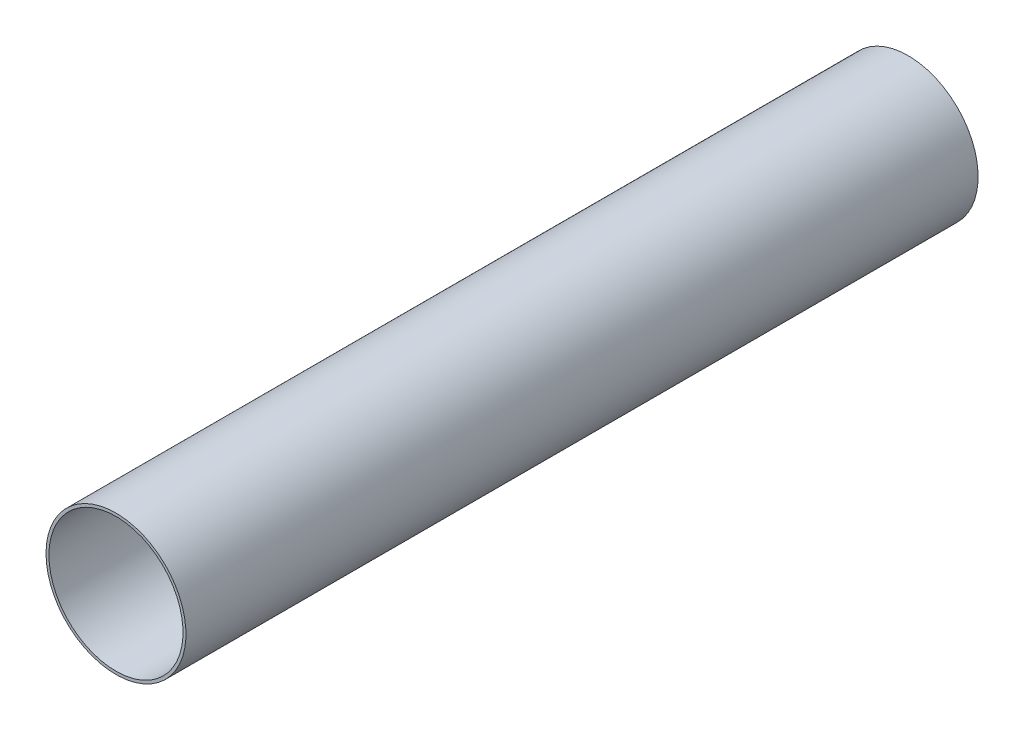
SolidWorks part; units mm, degrees
material "E-Glass Fiber"
ref_plane "Front Plane" through (0, 0, 0) normal (0, 0, 1) x (1, 0, 0)
ref_plane "Top Plane" through (0, 0, 0) normal (0, 1, 0) x (1, 0, 0)
ref_plane "Right Plane" through (0, 0, 0) normal (1, 0, 0) x (0, 0, -1)
sketch "Sketch1" plane through (0, 0, 0) normal (0, 0, 1) x (1, 0, 0)
  circle A0 centre (0, 0) radius 39.8145
  circle A1 centre (0, 0) radius 38.1635
  dimension "D1" = 79.629
  dimension "D2" = 76.327
extrude "Boss-Extrude1" add sketch "Sketch1" along normal blind 450.85
